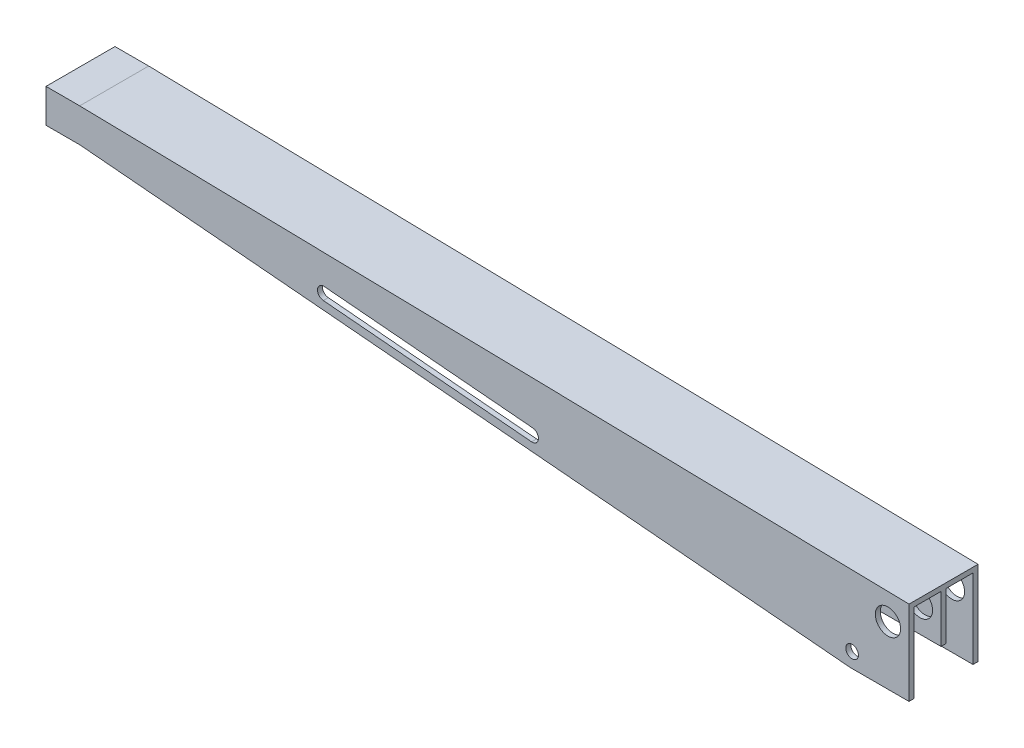
SolidWorks part; units mm, degrees
material "AISI 1045 Steel, cold drawn"
ref_plane "Front Plane" through (0, 0, 0) normal (0, 0, 1) x (1, 0, 0)
ref_plane "Top Plane" through (0, 0, 0) normal (0, 1, 0) x (1, 0, 0)
ref_plane "Right Plane" through (0, 0, 0) normal (1, 0, 0) x (0, 0, -1)
sketch "Sketch1" plane through (0, 0, 0) normal (0, 0, 1) x (1, 0, 0)
  line L0 (-2600, 304.8) -> (-2498.4, 304.8)
  line L1 (-2600, 304.8) -> (-2600, 203.2)
  line L2 (-2600, 203.2) -> (-2498.4, 203.2)
  line L4 (-177.8, 0) -> (0, 0)
  line L5 (0, 0) -> (0, 254)
  line L6 (0, 254) -> (-2498.4, 304.8)
  line L7 (-2498.4, 203.2) -> (-177.8, 0)
  dimension "D1" = 101.6
  dimension "D2" = 101.6
  dimension "D3" = 2600
  dimension "D4" = 177.8
  dimension "D6" = 203.2
  dimension "D7" = 254
extrude "Boss-Extrude1" add sketch "Sketch1" against normal blind 15
ref_plane "Plane1" through (0, 0, 177.8) normal (0, 0, 1) x (1, 0, 0)
sketch "Sketch2" plane through (0, 0, 177.8) normal (0, 0, 1) x (1, 0, 0)
  line L8 (-2498.4, 203.2) -> (-177.8, 0)
  line L10 (-177.8, 0) -> (0, 0)
  line L11 (0, 0) -> (0, 254)
  line L12 (0, 254) -> (-2498.4, 304.8)
  line L13 (-2498.4, 304.8) -> (-2600, 304.8)
  line L14 (-2600, 304.8) -> (-2600, 203.2)
  line L15 (-2600, 203.2) -> (-2498.4, 203.2)
  line L16 (-2498.4, 203.2) -> (-177.8, 0)
  line L18 (-177.8, 0) -> (0, 0)
  line L19 (0, 0) -> (0, 254)
  line L20 (0, 254) -> (-2498.4, 304.8)
  line L21 (-2498.4, 304.8) -> (-2600, 304.8)
  line L22 (-2600, 304.8) -> (-2600, 203.2)
  line L23 (-2600, 203.2) -> (-2498.4, 203.2)
  dimension "D1" = 0
extrude "Boss-Extrude2" add sketch "Sketch2" along normal blind 15 separate body
sketch "Sketch3" plane through (0, 0, 192.8) normal (0, 0, 1) x (1, 0, 0)
  line L6 (-2600, 289.8) -> (-2600, 304.8)
  line L7 (-2600, 304.8) -> (-2498.4, 304.8)
  line L8 (-2498.4, 304.8) -> (0, 254)
  line L9 (-15, 0) -> (-15, 239.3019)
  line L10 (-15, 239.3019) -> (-2498.5525, 289.8)
  line L11 (-2498.5525, 289.8) -> (-2600, 289.8)
  line L12 (-15, 239.3019) -> (0, 238.9969)
  line L13 (-15, 239.3019) -> (-2498.5525, 289.8)
  line L14 (-2498.5525, 289.8) -> (-2600, 289.8)
  line L15 (0, 0) -> (0, 254) construction
  line L16 (0, 238.9969) -> (0, 254)
  dimension "D1" = 15
extrude "Boss-Extrude3" add sketch "Sketch3" against normal up to surface (192.8 mm away) up to face at (-1482.0857, 181.4286, 0)
ref_plane "Plane2" through (0, 0, 88.9) normal (0, 0, 1) x (1, 0, 0)
sketch "Sketch6" plane through (0, 0, 88.9) normal (0, 0, 1) x (1, 0, 0)
  line L8 (-2498.4, 203.2) -> (-177.8, 0)
  line L10 (-177.8, 0) -> (0, 0)
  line L11 (0, 0) -> (0, 254)
  line L12 (0, 254) -> (-2498.4, 304.8)
  line L13 (-2498.4, 304.8) -> (-2600, 304.8)
  line L14 (-2600, 304.8) -> (-2600, 203.2)
  line L15 (-2600, 203.2) -> (-2498.4, 203.2)
  line L16 (-2498.4, 203.2) -> (-177.8, 0)
  line L18 (-177.8, 0) -> (0, 0)
  line L19 (0, 0) -> (0, 254)
  line L20 (0, 254) -> (-2498.4, 304.8)
  line L21 (-2498.4, 304.8) -> (-2600, 304.8)
  line L22 (-2600, 304.8) -> (-2600, 203.2)
  line L23 (-2600, 203.2) -> (-2498.4, 203.2)
  dimension "D1" = 0
extrude "Boss-Extrude4" add sketch "Sketch6" along normal blind 7.5 and the other way blind 7.5
sketch "Sketch5" plane through (0, 0, 192.8) normal (0, 0, 1) x (1, 0, 0)
  line L1 (0, 238.9969) -> (-2498.5525, 289.8) construction
  line L2 (-177.8, 0) -> (0, 0) construction
  line L3 (0, 0) -> (0, 254) construction
  circle A0 centre (-63.5, 176.7828) radius 38.1
  circle A1 centre (-171.45, 44.45) radius 19.05
  point P2 (-25.4, 176.7828)
  point P5 (-63.5, 214.8828)
  point P9 (-171.45, 25.4)
  point P10 (-190.5, 44.45)
  point P13 (-101.6, 176.7828)
  point P21 (-152.4, 44.45)
  dimension "D1" = 25.4
  dimension "D3" = 76.2
  dimension "D6" = 38.1
  dimension "D2" = 25.4
  dimension "D4" = 25.4
  dimension "D5" = 50.8
extrude "Cut-Extrude1" cut sketch "Sketch5" against normal through all
sketch "Sketch7" plane through (0, 0, 96.4) normal (0, 0, 1) x (1, 0, 0)
  line L0 (-1265.5813, 95.25) -> (0, 95.25)
  line L1 (0, 95.25) -> (0, 0)
  line L2 (0, 0) -> (-177.8, 0)
  line L3 (-177.8, 0) -> (0, 0) construction
  line L4 (0, 0) -> (0, 238.9969) construction
  line L5 (-2498.4, 203.2) -> (-177.8, 0) construction
  line L6 (-1265.5813, 95.25) -> (-177.8, 0)
  dimension "D1" = 95.25
extrude "Cut-Extrude2" cut sketch "Sketch7" against normal up to surface (15 mm away) up to face at (-152.4, 44.45, 81.4)
sketch "Sketch8" plane through (0, 304.8, 0) normal (0, 1, 0) x (1, 0, 0)
  line L0 (-2600, -88.9) -> (-2498.4, -88.9) construction
  line L1 (-2600, 15) -> (-2600, -192.8) construction
  line L2 (-2498.4, 15) -> (-2498.4, -192.8) construction
  line L3 (-2549.2, 15) -> (-2549.2, -192.8) construction
  line L4 (-2498.4, 15) -> (-2600, 15) construction
  line L5 (-2498.4, -192.8) -> (-2600, -192.8) construction
  circle A0 centre (-2549.2, -88.9) radius 25.4
  dimension "D1" = 50.8
sketch "Sketch10" [suppressed] plane through (0, 0, 81.4) normal (0, 0, -1) x (-1, 0, 0)
  line L0 (2498.4, 203.2) -> (177.8, 0) construction
  line L1 (2498.4, 203.2) -> (177.8, 0)
  line L2 (1462.4863, 237.5331) -> (1378.2421, 171.3211) construction
  line L3 (1462.4863, 237.5331) -> (1378.2421, 171.3211)
  line L4 (1462.4863, 237.5331) -> (1177.7732, 13.7621)
  line L5 (1177.7732, 13.7621) -> (2500.6133, 204.7162)
  line L6 (2500.6133, 204.7162) -> (2518.6944, 79.459)
  line L7 (2518.6944, 79.459) -> (1378.2421, 171.3211)
  line M5 (0, 95.25) -> (1265.5813, 95.25)
  line M6 (1265.5813, 95.25) -> (2498.4, 203.2)
  line M7 (2498.4, 203.2) -> (2600, 203.2)
extrude "Cut-Extrude5" [suppressed] cut sketch "Sketch10" against normal up to surface (96.4 mm away) contours L7 L6 L1 L3 M7 M6 | L3 L1 M5 | L6 L5 L4 L3 M5 M6 M7
sketch "Sketch11" [suppressed] plane through (0, 0, 81.4) normal (0, 0, -1) x (-1, 0, 0)
  line L0 (1102.8132, 95.25) -> (1054.7429, 95.25)
  line L1 (1102.8132, 95.25) -> (0, 95.25) construction
  line L2 (1103.8034, 107.8769) -> (1102.8132, 95.25) construction
  line L3 (1104.0385, 110.8746) -> (1102.8132, 95.25)
  line L4 (2423.9124, -959.3916) -> (1614.176, 70.8697) construction
  line L5 (2423.9124, -959.3916) -> (1614.176, 70.8697)
  line L6 (1614.176, 70.8697) -> (1104.0385, 110.8746)
  line L7 (2431.7747, -953.2122) -> (1619.3289, 80.4963)
  line L8 (1619.3289, 80.4963) -> (1094.8509, 121.6258)
  line L9 (1094.8509, 121.6258) -> (1092.8438, 96.0318)
  line L10 (2431.7747, -953.2122) -> (2423.9124, -959.3916)
  dimension "D1" = 10
extrude "Cut-Extrude6" [suppressed] cut sketch "Sketch11" against normal blind 60
sketch "Sketch13" plane through (0, 0, 81.4) normal (0, 0, -1) x (-1, 0, 0)
  line L1 (2605.2676, 259.0229) -> (2605.6242, 249.5947)
  line L6 (1105.7567, 0) -> (2612.8229, 133.8874)
  line L7 (2612.8229, 133.8874) -> (2605.6242, 249.5947)
  line L8 (2605.2676, 259.0229) -> (1249.0916, 207.7291)
  line L9 (1249.0916, 207.7291) -> (1091.7204, 201.777)
  line L10 (1091.7204, 201.777) -> (1095.7638, 94.872)
  line L11 (1095.7638, 94.872) -> (1095.7638, 0)
  line L12 (1095.7638, 0) -> (1105.7567, 0)
extrude "Cut-Extrude12" cut sketch "Sketch13" against normal blind 60
sketch "Sketch14" plane through (0, 0, -15) normal (0, 0, -1) x (-1, 0, 0)
  line L0 (0, 0) -> (0, 254) construction
  line L1 (0, 254) -> (2498.4, 304.8) construction
  circle A0 centre (1175.0161, 131.2762) radius 19.05 construction
  circle A1 centre (1175.0161, 131.2762) radius 19.05
  dimension "D1" = 1175.0161
  dimension "D2" = 146.5852
extrude "Cut-Extrude14" [suppressed] cut sketch "Sketch14" against normal through all both and the other way through all
sketch "Sketch15" [suppressed] plane through (0, 0, -15) normal (0, 0, -1) x (-1, 0, 0)
  line L9 (2600, 203.2) -> (2600, 304.8)
  line L10 (2600, 304.8) -> (2498.4, 304.8)
  line L11 (2498.4, 304.8) -> (0, 254)
  line L12 (0, 254) -> (0, 0)
  line L13 (0, 0) -> (177.8, 0)
  line L14 (177.8, 0) -> (2498.4, 203.2)
  line L15 (2498.4, 203.2) -> (2600, 203.2)
  line L16 (2600, 203.2) -> (2600, 304.8)
  line L17 (2600, 304.8) -> (2498.4, 304.8)
  line L18 (2498.4, 304.8) -> (0, 254)
  line L19 (0, 254) -> (0, 0)
  line L20 (0, 0) -> (177.8, 0)
  line L21 (177.8, 0) -> (2498.4, 203.2)
  line L22 (2498.4, 203.2) -> (2600, 203.2)
  circle A0 centre (1135.458, 127.7936) radius 19.05 construction
  circle A1 centre (1135.458, 127.7936) radius 19.05
  dimension "D4" = 0
extrude "Cut-Extrude15" [suppressed] cut sketch "Sketch15" against normal through all both and the other way through all
sketch "Sketch16" plane through (0, 0, -15) normal (0, 0, -1) x (-1, 0, 0)
  line L0 (0, 0) -> (0, 254) construction
  line L1 (0, 254) -> (2498.4, 304.8) construction
  circle A0 centre (1135.4588, 127.8124) radius 19.05
  dimension "D1" = 1135.4588
  dimension "D3" = 38.1
  dimension "D2" = 149.2441
extrude "Cut-Extrude16" cut sketch "Sketch16" against normal through all both and the other way through all
sketch "Sketch17" plane through (0, 0, -15) normal (0, 0, -1) x (-1, 0, 0)
  line L0 (1135.4588, 127.8124) -> (1763.0574, 182.7672) construction
  line L1 (1133.7971, 146.7898) -> (1761.3957, 201.7445)
  line L2 (1137.1206, 108.835) -> (1764.7192, 163.7898)
  line L3 (2498.4, 203.2) -> (177.8, 0) construction
  arc A0 (1133.7971, 146.7898) -> (1137.1206, 108.835) centre (1135.4588, 127.8124) ccw
  arc A1 (1764.7192, 163.7898) -> (1761.3957, 201.7445) centre (1763.0574, 182.7672) ccw
  point P3 (1449.2581, 155.2898)
  dimension "D1" = 19.05
  dimension "D2" = 630
extrude "Cut-Extrude17" cut sketch "Sketch17" against normal through all both and the other way through all
sketch "Sketch18" plane through (0, 0, 81.4) normal (0, 0, -1) x (-1, 0, 0)
  line L1 (1091.7204, 201.777) -> (1051.7954, 201.777)
  line L2 (1091.7204, 201.777) -> (1091.7204, 86.7146)
  line L3 (1091.7204, 86.7146) -> (1051.7954, 86.7146)
  line L4 (1051.7954, 201.777) -> (1051.7954, 86.7146)
  line L5 (1091.7204, 201.777) -> (1110.0396, 201.777)
  line L6 (1091.7204, 201.777) -> (1091.7204, 86.7146)
  line L7 (1091.7204, 86.7146) -> (1110.0396, 86.7146)
  line L8 (1110.0396, 201.777) -> (1110.0396, 86.7146)
  line M2 (0, 95.25) -> (1095.7495, 95.25)
  line M3 (1095.7495, 95.25) -> (1091.7204, 201.777)
extrude "Cut-Extrude18" cut sketch "Sketch18" against normal up to surface (96.4 mm away) contours L1 L4 L2 M2 | L8 L5 L2 L7 M3 M2 up to face at (-1449.2581, 155.2898, 177.8)
